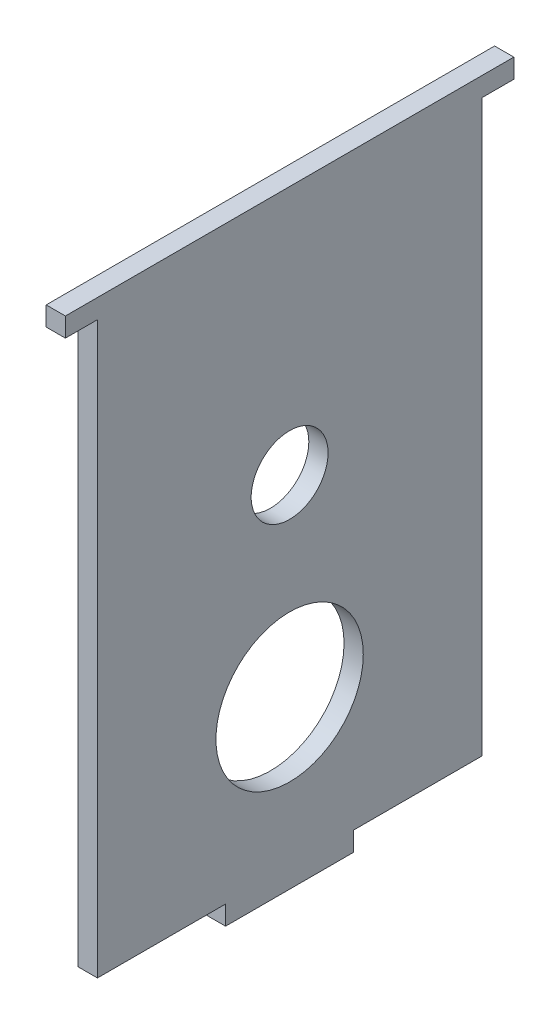
SolidWorks part; units mm, degrees
ref_plane "Front Plane" through (0, 0, 0) normal (0, 0, 1) x (1, 0, 0)
ref_plane "Top Plane" through (0, 0, 0) normal (0, 1, 0) x (1, 0, 0)
ref_plane "Right Plane" through (0, 0, 0) normal (1, 0, 0) x (0, 0, -1)
sketch "Sketch1" plane through (0, 0, 0) normal (1, 0, 0) x (0, 0, -1)
  line L1 (-30, 48) -> (30, 48)
  line L2 (-30, 48) -> (-30, -48)
  line L3 (-30, -48) -> (30, -48)
  line L4 (30, 48) -> (30, -48)
  line L5 (-30, 48) -> (30, -48) construction
  line L6 (-30, -48) -> (30, 48) construction
  point P0 (0, 0)
  dimension "D1" = 96
  dimension "D2" = 60
extrude "Boss-Extrude1" add sketch "Sketch1" along normal blind 3
sketch "Sketch2" plane through (3, 0, 0) normal (1, 0, 0) x (0, 0, -1)
  line L0 (0, 0) -> (0, -25) construction
  line L1 (0, 0) -> (0, 5) construction
  circle A0 centre (0, -25) radius 11.5
  circle A1 centre (0, 5) radius 6
  dimension "D2" = 23
  dimension "D3" = 12
  dimension "D1" = 25
  dimension "D4" = 5
extrude "Cut-Extrude1" cut sketch "Sketch2" against normal blind 3
sketch "Sketch3" plane through (0, 0, 0) normal (1, 0, 0) x (0, 0, -1)
  line L0 (-30, 41) -> (-35, 41)
  line L1 (-35, 41) -> (-35, 44)
  line L2 (-35, 44) -> (-30, 44)
  line L3 (-30, 48) -> (-30, -48) construction
  line L4 (30, 41) -> (35, 41)
  line L5 (35, 41) -> (35, 44)
  line L6 (35, 44) -> (30, 44)
  line L7 (30, -48) -> (30, 48) construction
  line L8 (-30, 44) -> (-30, 41)
  line L9 (30, 44) -> (30, 41)
  line L10 (-10, -48) -> (-10, -51)
  line L11 (30, 48) -> (-30, 48) construction
  line L12 (-30, -48) -> (30, -48) construction
  line L13 (-10, -51) -> (10, -51)
  line L14 (10, -51) -> (10, -48)
  line L15 (-10, -48) -> (10, -48)
  dimension "D1" = 3
  dimension "D2" = 5
  dimension "D3" = 4
  dimension "D4" = 4
  dimension "D5" = 20
  dimension "D6" = 3
extrude "Boss-Extrude2" add sketch "Sketch3" along normal blind 3
sketch "Sketch4" plane through (0, 0, 35) normal (0, 0, 1) x (1, 0, 0)
  line L0 (0, 44) -> (3, 41) construction
  line L1 (3, 41) -> (0, 41) construction
  line L2 (0, 41) -> (3, 44) construction
  circle A0 centre (1.5, 42.5) radius 1.1361
sketch "Sketch6" plane through (3, 0, 0) normal (1, 0, 0) x (0, 0, -1)
  line L0 (-30, 44) -> (30, 44)
  line L1 (30, 44) -> (30, 48)
  line L2 (30, 48) -> (-30, 48)
  line L3 (-30, 48) -> (-30, 44)
extrude "Cut-Extrude2" cut sketch "Sketch6" against normal blind 10
